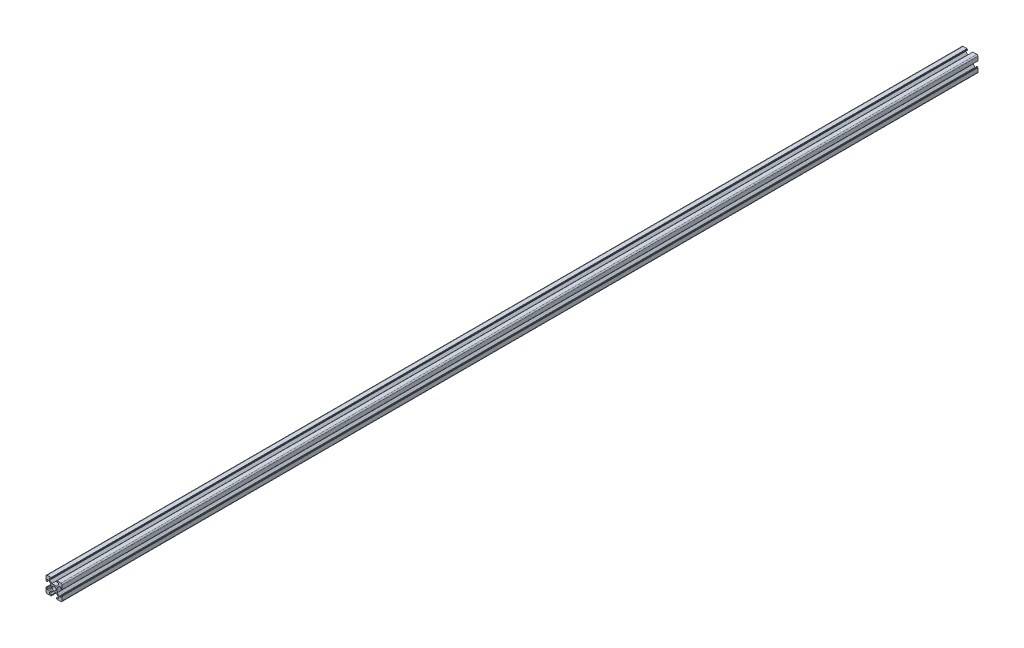
SolidWorks part; units mm, degrees
ref_plane "前视基准面" through (0, 0, 0) normal (0, 0, 1) x (1, 0, 0)
ref_plane "上视基准面" through (0, 0, 0) normal (0, 1, 0) x (1, 0, 0)
ref_plane "右视基准面" through (0, 0, 0) normal (1, 0, 0) x (0, 0, -1)
other "Configuration Table"
sketch "草图1" plane through (0, 0, 0) normal (1, 0, 0) x (0, 0, -1)
  line L0 (0, 0) -> (1144, 0)
  dimension "D1" = 1144
other "铝型材 20 X 20 X R1.5(1)"
ref_plane "基准面1" through (0, 0, 0) normal (0, 0, -1) x (0, 1, 0)
sketch "Sketch1" plane through (0, 0, 0) normal (0, 0, -1) x (0, 1, 0)
  line L0 (-3.6, 10) -> (-3.6, 9.5)
  line L1 (-3.6, 9.5) -> (-3.1, 9.5)
  line L2 (-3.1, 9.5) -> (-3.1, 8.5)
  line L3 (-3.1, 8.5) -> (-5.5, 8.5)
  line L4 (-8.5, -10) -> (-3.6, -10)
  line L5 (-10, -8.5) -> (-10, -3.6)
  line L6 (8.5, 10) -> (3.6, 10)
  line L7 (10, 8.5) -> (10, 3.6)
  line L8 (0, 14.8756) -> (0, 0) construction
  line L9 (0, 0) -> (14.1675, 0) construction
  line L10 (-5.5, 8.5) -> (-5.5, 6.65)
  line L11 (-5.5, 6.65) -> (-2.75, 3.9)
  line L12 (-2.75, 3.9) -> (2.75, 3.9)
  line L13 (5.5, 6.65) -> (2.75, 3.9)
  line L14 (5.5, 8.5) -> (5.5, 6.65)
  line L15 (3.1, 8.5) -> (5.5, 8.5)
  line L16 (3.1, 9.5) -> (3.1, 8.5)
  line L17 (3.6, 9.5) -> (3.1, 9.5)
  line L18 (3.6, 10) -> (3.6, 9.5)
  line L19 (-3.6, 10) -> (-8.5, 10)
  line L20 (10, 3.6) -> (9.5, 3.6)
  line L21 (9.5, 3.6) -> (9.5, 3.1)
  line L22 (9.5, 3.1) -> (8.5, 3.1)
  line L23 (8.5, 3.1) -> (8.5, 5.5)
  line L24 (8.5, 5.5) -> (6.65, 5.5)
  line L25 (6.65, 5.5) -> (3.9, 2.75)
  line L26 (3.9, 2.75) -> (3.9, -2.75)
  line L27 (6.65, -5.5) -> (3.9, -2.75)
  line L28 (8.5, -5.5) -> (6.65, -5.5)
  line L29 (8.5, -3.1) -> (8.5, -5.5)
  line L30 (9.5, -3.1) -> (8.5, -3.1)
  line L31 (9.5, -3.6) -> (9.5, -3.1)
  line L32 (10, -3.6) -> (9.5, -3.6)
  line L33 (3.6, -10) -> (3.6, -9.5)
  line L34 (3.6, -9.5) -> (3.1, -9.5)
  line L35 (3.1, -9.5) -> (3.1, -8.5)
  line L36 (3.1, -8.5) -> (5.5, -8.5)
  line L37 (5.5, -8.5) -> (5.5, -6.65)
  line L38 (5.5, -6.65) -> (2.75, -3.9)
  line L39 (2.75, -3.9) -> (-2.75, -3.9)
  line L40 (-5.5, -6.65) -> (-2.75, -3.9)
  line L41 (-5.5, -8.5) -> (-5.5, -6.65)
  line L42 (-3.1, -8.5) -> (-5.5, -8.5)
  line L43 (-3.1, -9.5) -> (-3.1, -8.5)
  line L44 (-3.6, -9.5) -> (-3.1, -9.5)
  line L45 (-3.6, -10) -> (-3.6, -9.5)
  line L46 (-10, -3.6) -> (-9.5, -3.6)
  line L47 (-9.5, -3.6) -> (-9.5, -3.1)
  line L48 (-9.5, -3.1) -> (-8.5, -3.1)
  line L49 (-8.5, -3.1) -> (-8.5, -5.5)
  line L50 (-8.5, -5.5) -> (-6.65, -5.5)
  line L51 (-6.65, -5.5) -> (-3.9, -2.75)
  line L52 (-3.9, -2.75) -> (-3.9, 2.75)
  line L53 (-6.65, 5.5) -> (-3.9, 2.75)
  line L54 (-8.5, 5.5) -> (-6.65, 5.5)
  line L55 (-8.5, 3.1) -> (-8.5, 5.5)
  line L56 (-9.5, 3.1) -> (-8.5, 3.1)
  line L57 (-9.5, 3.6) -> (-9.5, 3.1)
  line L58 (-10, 3.6) -> (-9.5, 3.6)
  line L59 (3.6, -10) -> (8.5, -10)
  line L60 (-10, 3.6) -> (-10, 8.5)
  line L61 (10, -3.6) -> (10, -8.5)
  circle A0 centre (0, 0) radius 2.5
  arc A1 (-10, 8.5) -> (-8.5, 10) centre (-8.5, 8.5) cw
  arc A2 (10, 8.5) -> (8.5, 10) centre (8.5, 8.5) ccw
  arc A3 (-8.5, -10) -> (-10, -8.5) centre (-8.5, -8.5) cw
  arc A4 (8.5, -10) -> (10, -8.5) centre (8.5, -8.5) ccw
  point P0 (-10, 0)
  point P1 (10, 0)
  point P2 (0, 10)
  point P3 (0, -10)
  point P4 (0, 0)
  point P5 (-10, -10)
  point P6 (10, -10)
  point P7 (10, 10)
  point P8 (-10, 10)
  point P13 (0, 0)
  point P36 (-10, 10)
  point P39 (10, 10)
  dimension "D1" = 11
  dimension "D2" = 20
  dimension "D3" = 6.2
  dimension "D4" = 7.2
  dimension "D5" = 6.1
  dimension "D6" = 5
  dimension "D7" = 1.5
  dimension "D8" = 45
  dimension "D9" = 0.5
  dimension "D10" = 1
  dimension "D11" = 5.5
